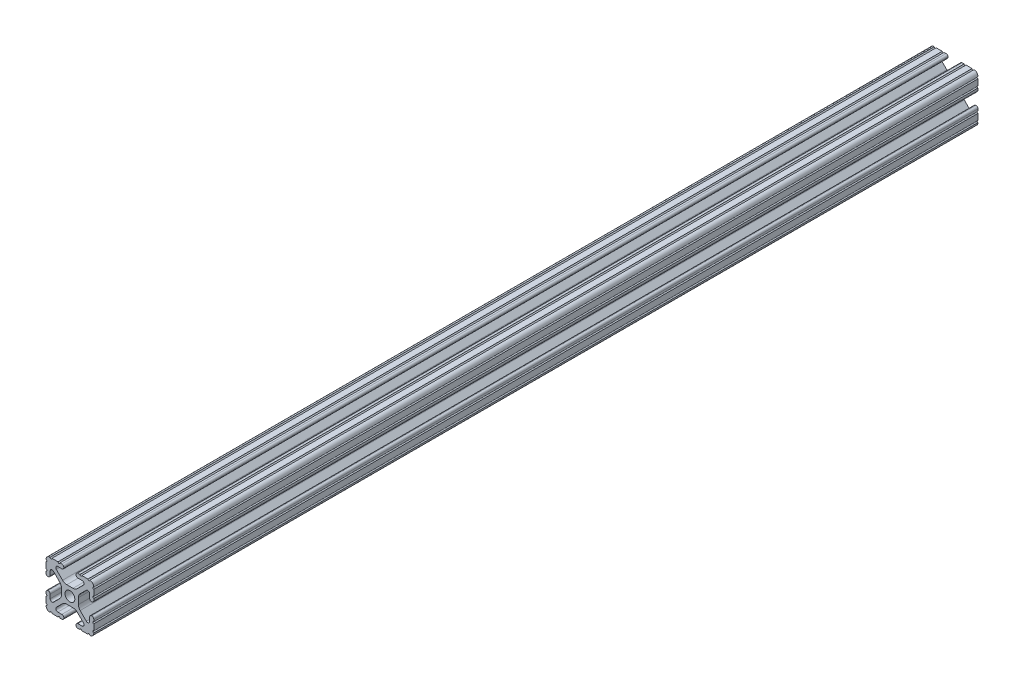
SolidWorks part; units mm, degrees
ref_plane "Front Plane" through (0, 0, 0) normal (0, 0, 1) x (1, 0, 0)
ref_plane "Top Plane" through (0, 0, 0) normal (0, 1, 0) x (1, 0, 0)
ref_plane "Right Plane" through (0, 0, 0) normal (1, 0, 0) x (0, 0, -1)
sketch "Sketch1" plane through (0, 0, 0) normal (0, 0, 1) x (1, 0, 0)
  line L88 (-7.1797, -8.6452) -> (-3.9523, -5.4237)
  line L89 (-1.7093, -4.4958) -> (1.7093, -4.4958)
  line L90 (3.9523, -5.4237) -> (7.1797, -8.6452)
  line L91 (6.4164, -10.4902) -> (4.2875, -10.4902)
  line L92 (3.2385, -11.5392) -> (3.2385, -11.651)
  line L93 (4.2875, -12.7) -> (5.3171, -12.7)
  line L94 (6.3331, -12.7) -> (9.5504, -12.7)
  line L95 (12.7, -9.5504) -> (12.7, -6.3331)
  line L96 (12.7, -5.3171) -> (12.7, -4.2875)
  line L97 (11.651, -3.2385) -> (11.5392, -3.2385)
  line L98 (10.4902, -4.2875) -> (10.4902, -6.4021)
  line L99 (8.7371, -7.1294) -> (5.441, -3.8408)
  line L100 (4.5085, -1.5932) -> (4.5085, 1.5932)
  line L101 (5.441, 3.8408) -> (8.7371, 7.1294)
  line L102 (10.4902, 6.4021) -> (10.4902, 4.2875)
  line L103 (11.5392, 3.2385) -> (11.651, 3.2385)
  line L104 (12.7, 4.2875) -> (12.7, 5.3171)
  line L105 (12.7, 6.3331) -> (12.7, 9.5504)
  line L106 (9.5504, 12.7) -> (6.3331, 12.7)
  line L107 (5.3171, 12.7) -> (4.2875, 12.7)
  line L108 (3.2385, 11.651) -> (3.2385, 11.5392)
  line L109 (4.2875, 10.4902) -> (6.4768, 10.4902)
  line L110 (7.207, 8.7244) -> (3.8983, 5.4232)
  line L111 (1.6558, 4.4958) -> (-1.6558, 4.4958)
  line L112 (-3.8983, 5.4232) -> (-7.207, 8.7244)
  line L113 (-6.4768, 10.4902) -> (-4.2875, 10.4902)
  line L114 (-3.2385, 11.5392) -> (-3.2385, 11.651)
  line L115 (-4.2875, 12.7) -> (-5.3171, 12.7)
  line L116 (-6.3331, 12.7) -> (-9.5504, 12.7)
  line L117 (-12.7, 9.5504) -> (-12.7, 6.3331)
  line L118 (-12.7, 5.3171) -> (-12.7, 4.2875)
  line L119 (-11.651, 3.2385) -> (-11.5392, 3.2385)
  line L120 (-10.4902, 4.2875) -> (-10.4902, 6.4021)
  line L121 (-8.7371, 7.1294) -> (-5.441, 3.8408)
  line L122 (-4.5085, 1.5932) -> (-4.5085, -1.5932)
  line L123 (-5.441, -3.8408) -> (-8.7371, -7.1294)
  line L124 (-10.4902, -6.4021) -> (-10.4902, -4.2875)
  line L125 (-11.5392, -3.2385) -> (-11.651, -3.2385)
  line L126 (-12.7, -4.2875) -> (-12.7, -5.3171)
  line L127 (-12.7, -6.3331) -> (-12.7, -9.5504)
  line L128 (-9.5504, -12.7) -> (-6.3331, -12.7)
  line L129 (-5.3171, -12.7) -> (-4.2875, -12.7)
  line L130 (-3.2385, -11.651) -> (-3.2385, -11.5392)
  line L131 (-4.2875, -10.4902) -> (-6.4164, -10.4902)
  circle A1 centre (0, 0) radius 2.6035
  arc A104 (-7.1797, -8.6452) -> (-6.4164, -10.4902) centre (-6.4164, -9.4098) ccw
  arc A105 (-1.7093, -4.4958) -> (-3.9523, -5.4237) centre (-1.7093, -7.6708) ccw
  arc A106 (3.9523, -5.4237) -> (1.7093, -4.4958) centre (1.7093, -7.6708) ccw
  arc A107 (6.4164, -10.4902) -> (7.1797, -8.6452) centre (6.4164, -9.4098) ccw
  arc A108 (4.2875, -10.4902) -> (3.2385, -11.5392) centre (4.2875, -11.5392) ccw
  arc A109 (3.2385, -11.651) -> (4.2875, -12.7) centre (4.2875, -11.651) ccw
  arc A110 (6.3331, -12.7) -> (5.3171, -12.7) centre (5.8251, -12.7) ccw
  arc A111 (10.5664, -12.6998) -> (9.5504, -12.7) centre (10.0584, -12.7) ccw
  arc A112 (10.5664, -12.6998) -> (12.6998, -10.5664) centre (10.5918, -10.5918) ccw
  arc A113 (12.7, -9.5504) -> (12.6998, -10.5664) centre (12.7, -10.0584) ccw
  arc A114 (12.7, -5.3171) -> (12.7, -6.3331) centre (12.7, -5.8251) ccw
  arc A115 (12.7, -4.2875) -> (11.651, -3.2385) centre (11.651, -4.2875) ccw
  arc A116 (11.5392, -3.2385) -> (10.4902, -4.2875) centre (11.5392, -4.2875) ccw
  arc A117 (8.7371, -7.1294) -> (10.4902, -6.4021) centre (9.4628, -6.4021) ccw
  arc A118 (4.5085, -1.5932) -> (5.441, -3.8408) centre (7.6835, -1.5932) ccw
  arc A119 (5.441, 3.8408) -> (4.5085, 1.5932) centre (7.6835, 1.5932) ccw
  arc A120 (10.4902, 6.4021) -> (8.7371, 7.1294) centre (9.4628, 6.4021) ccw
  arc A121 (10.4902, 4.2875) -> (11.5392, 3.2385) centre (11.5392, 4.2875) ccw
  arc A122 (11.651, 3.2385) -> (12.7, 4.2875) centre (11.651, 4.2875) ccw
  arc A123 (12.7, 6.3331) -> (12.7, 5.3171) centre (12.7, 5.8251) ccw
  arc A124 (12.6998, 10.5664) -> (12.7, 9.5504) centre (12.7, 10.0584) ccw
  arc A125 (12.6998, 10.5664) -> (10.5664, 12.6998) centre (10.5918, 10.5918) ccw
  arc A126 (9.5504, 12.7) -> (10.5664, 12.6998) centre (10.0584, 12.7) ccw
  arc A127 (5.3171, 12.7) -> (6.3331, 12.7) centre (5.8251, 12.7) ccw
  arc A128 (4.2875, 12.7) -> (3.2385, 11.651) centre (4.2875, 11.651) ccw
  arc A129 (3.2385, 11.5392) -> (4.2875, 10.4902) centre (4.2875, 11.5392) ccw
  arc A130 (7.207, 8.7244) -> (6.4768, 10.4902) centre (6.4768, 9.4563) ccw
  arc A131 (1.6558, 4.4958) -> (3.8983, 5.4232) centre (1.6558, 7.6708) ccw
  arc A132 (-3.8983, 5.4232) -> (-1.6558, 4.4958) centre (-1.6558, 7.6708) ccw
  arc A133 (-6.4768, 10.4902) -> (-7.207, 8.7244) centre (-6.4768, 9.4563) ccw
  arc A134 (-4.2875, 10.4902) -> (-3.2385, 11.5392) centre (-4.2875, 11.5392) ccw
  arc A135 (-3.2385, 11.651) -> (-4.2875, 12.7) centre (-4.2875, 11.651) ccw
  arc A136 (-6.3331, 12.7) -> (-5.3171, 12.7) centre (-5.8251, 12.7) ccw
  arc A137 (-10.5664, 12.6998) -> (-9.5504, 12.7) centre (-10.0584, 12.7) ccw
  arc A138 (-10.5664, 12.6998) -> (-12.6998, 10.5664) centre (-10.5918, 10.5918) ccw
  arc A139 (-12.7, 9.5504) -> (-12.6998, 10.5664) centre (-12.7, 10.0584) ccw
  arc A140 (-12.7, 5.3171) -> (-12.7, 6.3331) centre (-12.7, 5.8251) ccw
  arc A141 (-12.7, 4.2875) -> (-11.651, 3.2385) centre (-11.651, 4.2875) ccw
  arc A142 (-11.5392, 3.2385) -> (-10.4902, 4.2875) centre (-11.5392, 4.2875) ccw
  arc A143 (-8.7371, 7.1294) -> (-10.4902, 6.4021) centre (-9.4628, 6.4021) ccw
  arc A144 (-4.5085, 1.5932) -> (-5.441, 3.8408) centre (-7.6835, 1.5932) ccw
  arc A145 (-5.441, -3.8408) -> (-4.5085, -1.5932) centre (-7.6835, -1.5932) ccw
  arc A146 (-10.4902, -6.4021) -> (-8.7371, -7.1294) centre (-9.4628, -6.4021) ccw
  arc A147 (-10.4902, -4.2875) -> (-11.5392, -3.2385) centre (-11.5392, -4.2875) ccw
  arc A148 (-11.651, -3.2385) -> (-12.7, -4.2875) centre (-11.651, -4.2875) ccw
  arc A149 (-12.7, -6.3331) -> (-12.7, -5.3171) centre (-12.7, -5.8251) ccw
  arc A150 (-12.6998, -10.5664) -> (-12.7, -9.5504) centre (-12.7, -10.0584) ccw
  arc A151 (-12.6998, -10.5664) -> (-10.5664, -12.6998) centre (-10.5918, -10.5918) ccw
  arc A152 (-9.5504, -12.7) -> (-10.5664, -12.6998) centre (-10.0584, -12.7) ccw
  arc A153 (-5.3171, -12.7) -> (-6.3331, -12.7) centre (-5.8251, -12.7) ccw
  arc A154 (-4.2875, -12.7) -> (-3.2385, -11.651) centre (-4.2875, -11.651) ccw
  arc A155 (-3.2385, -11.5392) -> (-4.2875, -10.4902) centre (-4.2875, -11.5392) ccw
extrude "Boss-Extrude1" add sketch "Sketch1" along normal mid plane 469.9
